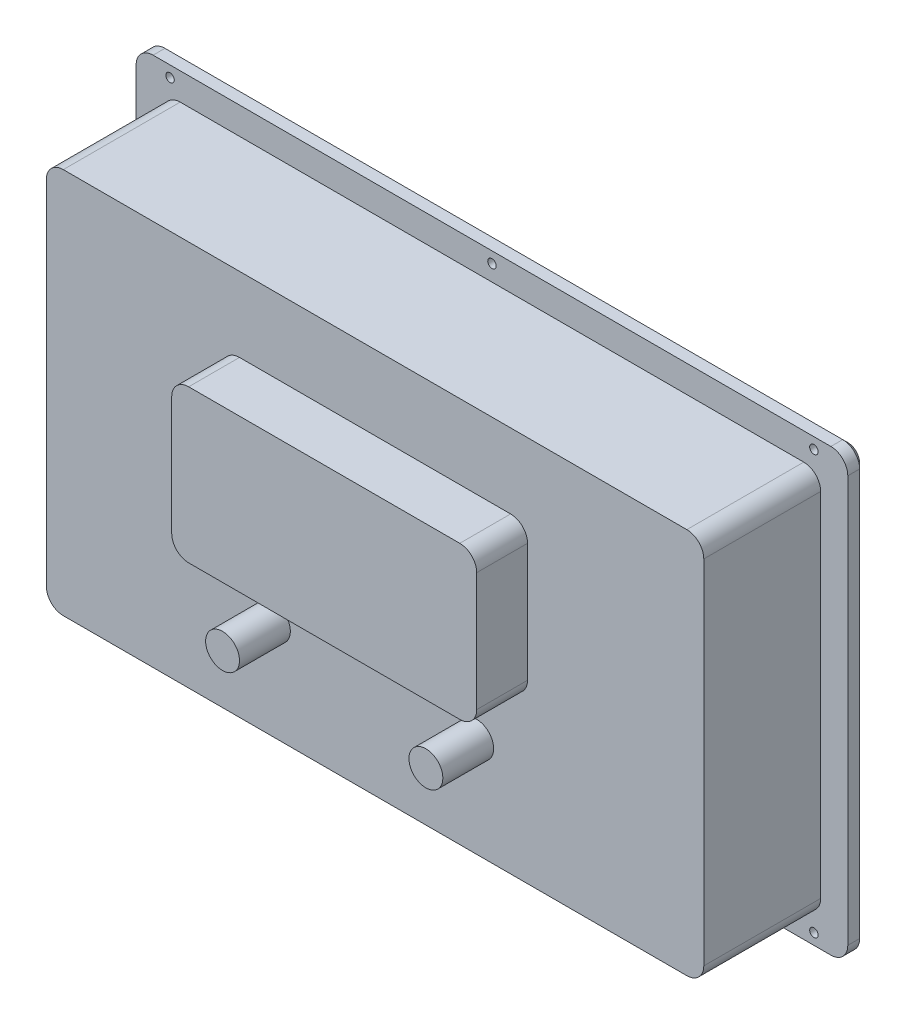
SolidWorks part; units mm, degrees
ref_plane "前视基准面" through (0, 0, 0) normal (0, 0, 1) x (1, 0, 0)
ref_plane "上视基准面" through (0, 0, 0) normal (0, 1, 0) x (1, 0, 0)
ref_plane "右视基准面" through (0, 0, 0) normal (1, 0, 0) x (0, 0, -1)
sketch "草图1" plane through (0, 0, 0) normal (0, 0, 1) x (1, 0, 0)
  line L1 (-210, -130) -> (210, -130)
  line L2 (-210, -130) -> (-210, 130)
  line L3 (-210, 130) -> (210, 130)
  line L4 (210, -130) -> (210, 130)
  line L5 (-210, -130) -> (210, 130) construction
  line L6 (-210, 130) -> (210, -130) construction
  point P0 (0, 0)
  dimension "D1" = 420
  dimension "D2" = 260
extrude "凸台-拉伸1" add sketch "草图1" along normal blind 10
sketch "草图2" plane through (0, 0, 10) normal (0, 0, 1) x (1, 0, 0)
  line L0 (210, 130) -> (-210, 130) construction
  line L1 (-194, -114) -> (194, -114)
  line L2 (-194, -114) -> (-194, 114)
  line L3 (-194, 114) -> (194, 114)
  line L4 (194, -114) -> (194, 114)
  line L5 (-194, -114) -> (194, 114) construction
  line L6 (-194, 114) -> (194, -114) construction
  line L7 (210, -130) -> (210, 130) construction
  point P0 (0, 0)
  dimension "D1" = 16
  dimension "D2" = 16
extrude "凸台-拉伸2" add sketch "草图2" along normal blind 69
sketch "草图3" plane through (0, 0, 79) normal (0, 0, 1) x (1, 0, 0)
  line L0 (0, 0) -> (0, 25) construction
  line L1 (-90, -20) -> (90, -20)
  line L2 (-90, -20) -> (-90, 70)
  line L3 (-90, 70) -> (90, 70)
  line L4 (90, -20) -> (90, 70)
  line L5 (-90, -20) -> (90, 70) construction
  line L6 (-90, 70) -> (90, -20) construction
  line L7 (0, 25) -> (0, -55) construction
  line L8 (-60, -55) -> (60, -55) construction
  circle A0 centre (-60, -55) radius 10
  circle A1 centre (60, -55) radius 10
  point P0 (0, 25)
  point P12 (0, -55)
  dimension "D6" = 20
  dimension "D1" = 25
  dimension "D2" = 90
  dimension "D3" = 180
  dimension "D4" = 120
  dimension "D5" = 80
extrude "凸台-拉伸3" add sketch "草图3" along normal blind 30
sketch "草图4" plane through (0, 0, 0) normal (0, 0, -1) x (-1, 0, 0)
  line L0 (0, 123.5) -> (0, -123.5) construction
  line L1 (-190, -123.5) -> (190, -123.5) construction
  line L2 (-190, -123.5) -> (-190, 123.5) construction
  line L3 (-190, 123.5) -> (190, 123.5) construction
  line L4 (190, -123.5) -> (190, 123.5) construction
  line L5 (-190, -123.5) -> (190, 123.5) construction
  line L6 (-190, 123.5) -> (190, -123.5) construction
  circle A0 centre (-190, 123.5) radius 2.5
  circle A1 centre (0, 123.5) radius 2.5
  circle A2 centre (190, 123.5) radius 2.5
  circle A3 centre (190, -123.5) radius 2.5
  circle A4 centre (0, -123.5) radius 2.5
  circle A5 centre (-190, -123.5) radius 2.5
  point P0 (0, 0)
  dimension "D3" = 5
  dimension "D1" = 380
  dimension "D2" = 247
extrude "切除-拉伸1" cut sketch "草图4" against normal through all
fillet "圆角1" radius 10 12 edges at (210, -130, 5) (-210, -130, 5) (-210, 130, 5) (210, 130, 5) (-90, -20, 94) (-90, 70, 94) (90, -20, 94) (90, 70, 94) (194, 114, 44.5) (194, -114, 44.5) (-194, -114, 44.5) (-194, 114, 44.5)
sketch "草图5" plane through (0, 0, 0) normal (0, 0, -1) x (-1, 0, 0)
  line L0 (-200, 130) -> (200, 130) construction
  line L1 (-165, 0) -> (-15, 0)
  line L2 (-170, 5) -> (-170, 95)
  line L3 (-165, 100) -> (-15, 100)
  line L4 (-10, 5) -> (-10, 95)
  line L5 (-170, 0) -> (-10, 100) construction
  line L6 (-170, 100) -> (-10, 0) construction
  line L7 (45, 0) -> (135, 0)
  line L8 (40, 5) -> (40, 95)
  line L9 (45, 100) -> (135, 100)
  line L10 (140, 5) -> (140, 95)
  line L11 (40, 0) -> (140, 100) construction
  line L12 (40, 100) -> (140, 0) construction
  line L13 (-145, -80) -> (145, -80)
  line L14 (-150, -75) -> (-150, -35)
  line L15 (-145, -30) -> (145, -30)
  line L16 (150, -75) -> (150, -35)
  line L17 (-150, -80) -> (150, -30) construction
  line L18 (-150, -30) -> (150, -80) construction
  line L19 (0, -55) -> (0, 0) construction
  arc A0 (-145, -30) -> (-150, -35) centre (-145, -35) ccw
  arc A1 (-150, -75) -> (-145, -80) centre (-145, -75) ccw
  arc A2 (145, -80) -> (150, -75) centre (145, -75) ccw
  arc A3 (150, -35) -> (145, -30) centre (145, -35) ccw
  arc A4 (135, 0) -> (140, 5) centre (135, 5) ccw
  arc A5 (140, 95) -> (135, 100) centre (135, 95) ccw
  arc A6 (45, 100) -> (40, 95) centre (45, 95) ccw
  arc A7 (40, 5) -> (45, 0) centre (45, 5) ccw
  arc A8 (-170, 5) -> (-165, 0) centre (-165, 5) ccw
  arc A9 (-10, 5) -> (-15, 0) centre (-15, 5) cw
  arc A10 (-10, 95) -> (-15, 100) centre (-15, 95) ccw
  arc A11 (-165, 100) -> (-170, 95) centre (-165, 95) ccw
  point P0 (-90, 50)
  point P5 (90, 50)
  point P10 (0, -55)
  dimension "D10" = 5
  dimension "D1" = 100
  dimension "D2" = 160
  dimension "D3" = 50
  dimension "D4" = 10
  dimension "D5" = 100
  dimension "D6" = 30
  dimension "D7" = 50
  dimension "D8" = 30
  dimension "D9" = 300
extrude "切除-拉伸2" cut sketch "草图5" against normal blind 0.5
chamfer "倒角1" distance 3 angle 45 8 edges at (0, -130, 0) (207.0711, -127.0711, 0) (-207.0711, -127.0711, 0) (210, 0, 0) (-210, 0, 0) (207.0711, 127.0711, 0) (-207.0711, 127.0711, 0) (0, 130, 0)
